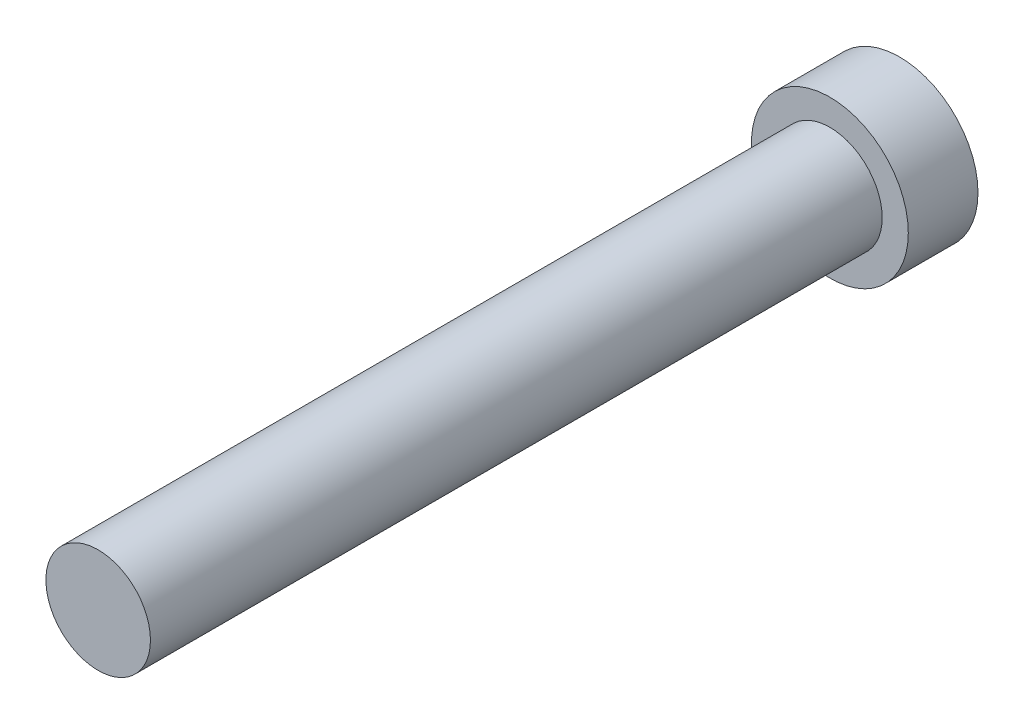
SolidWorks part; units mm, degrees
ref_plane "Front Plane" through (0, 0, 0) normal (0, 0, 1) x (1, 0, 0)
ref_plane "Top Plane" through (0, 0, 0) normal (0, 1, 0) x (1, 0, 0)
ref_plane "Right Plane" through (0, 0, 0) normal (1, 0, 0) x (0, 0, -1)
sketch "Sketch1" plane through (0, 0, 0) normal (0, 0, 1) x (1, 0, 0)
  circle A0 centre (0, 0) radius 22.5
  dimension "D1" = 45
extrude "Boss-Extrude1" add sketch "Sketch1" along normal blind 20
sketch "Sketch2" plane through (0, 0, 20) normal (0, 0, 1) x (1, 0, 0)
  circle A0 centre (0, 0) radius 15
  dimension "D1" = 30
extrude "Boss-Extrude2" add sketch "Sketch2" along normal blind 210
